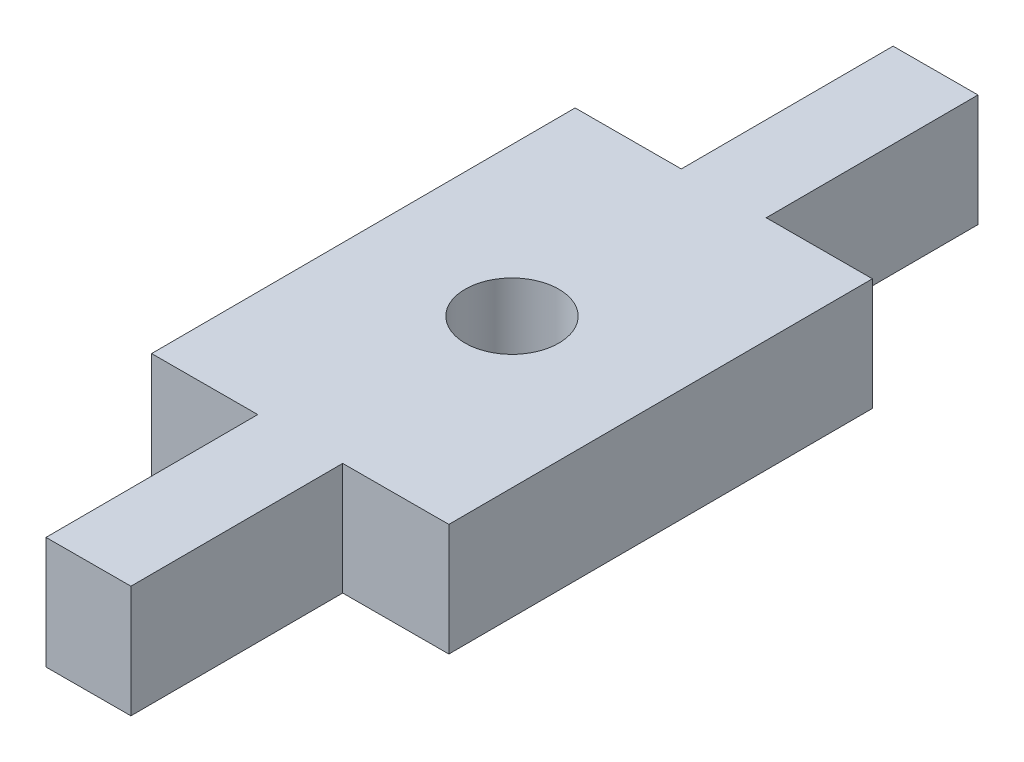
SolidWorks part; units mm, degrees
ref_plane "Front Plane" through (0, 0, 0) normal (0, 0, 1) x (1, 0, 0)
ref_plane "Top Plane" through (0, 0, 0) normal (0, 1, 0) x (1, 0, 0)
ref_plane "Right Plane" through (0, 0, 0) normal (1, 0, 0) x (0, 0, -1)
sketch "Sketch1" plane through (0, 0, 0) normal (0, 1, 0) x (1, 0, 0)
  line L0 (-1.1843, -6.0029) -> (-1.1709, -12.0032)
  line L1 (-1.1709, -12.0032) -> (1.2248, -11.9977)
  line L2 (1.2248, -11.9977) -> (1.2113, -5.9975)
  line L3 (1.2113, -5.9975) -> (4.206, -5.9906)
  line L4 (4.206, -5.9906) -> (4.1792, 6.0097)
  line L5 (4.1792, 6.0097) -> (1.1845, 6.003)
  line L6 (1.1845, 6.003) -> (1.1711, 12.0032)
  line L7 (1.1711, 12.0032) -> (-1.2245, 11.9978)
  line L8 (-1.2245, 11.9978) -> (-1.2111, 5.9976)
  line L9 (-1.2111, 5.9976) -> (-4.206, 5.9908)
  line L10 (-4.206, 5.9908) -> (-4.1791, -6.0095)
  line L11 (-4.1791, -6.0095) -> (-1.1843, -6.0029)
  line L12 (-0.9373, 0.9349) -> (0.9373, -0.9347) construction
  circle A0 centre (0, 0) radius 1.3237
extrude "Boss-Extrude1" add sketch "Sketch1" along normal blind 3.175
